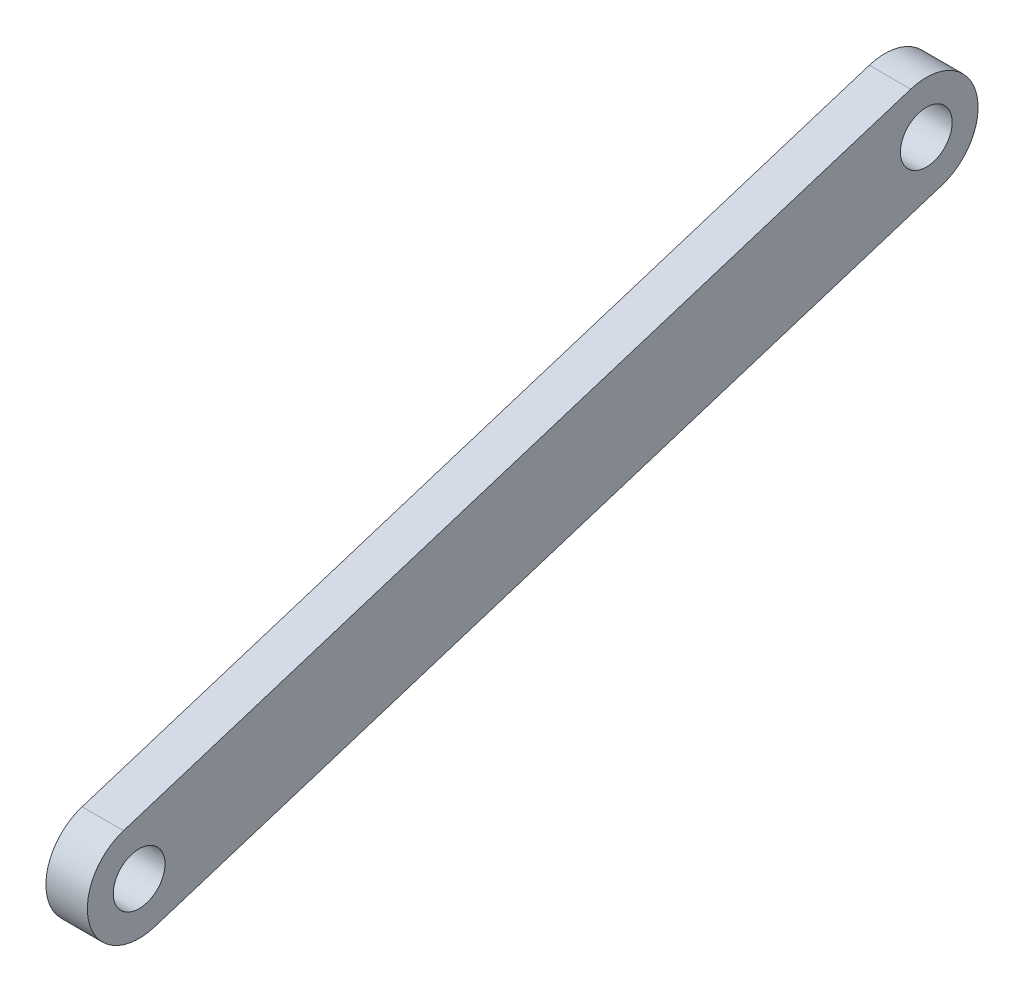
SolidWorks part; units mm, degrees
ref_plane "Front Plane" through (0, 0, 0) normal (0, 0, 1) x (1, 0, 0)
ref_plane "Top Plane" through (0, 0, 0) normal (0, 1, 0) x (1, 0, 0)
ref_plane "Right Plane" through (0, 0, 0) normal (1, 0, 0) x (0, 0, -1)
sketch "Sketch2" plane through (0, 0, 0) normal (1, 0, 0) x (0, 0, -1)
  line L0 (0, 0) -> (950, 300) construction
  line L1 (-18.8207, 59.5989) -> (931.1793, 359.5989)
  line L2 (18.8207, -59.5989) -> (968.8207, 240.4011)
  arc A0 (-18.8207, 59.5989) -> (18.8207, -59.5989) centre (0, 0) ccw
  arc A1 (968.8207, 240.4011) -> (931.1793, 359.5989) centre (950, 300) ccw
  circle A2 centre (0, 0) radius 31.25
  circle A3 centre (950, 300) radius 31.25
  point P3 (475, 150)
  dimension "D3" = 62.5
  dimension "D4" = 62.5
  dimension "D1" = 300
  dimension "D2" = 950
extrude "Boss-Extrude1" add sketch "Sketch2" along normal blind 50
